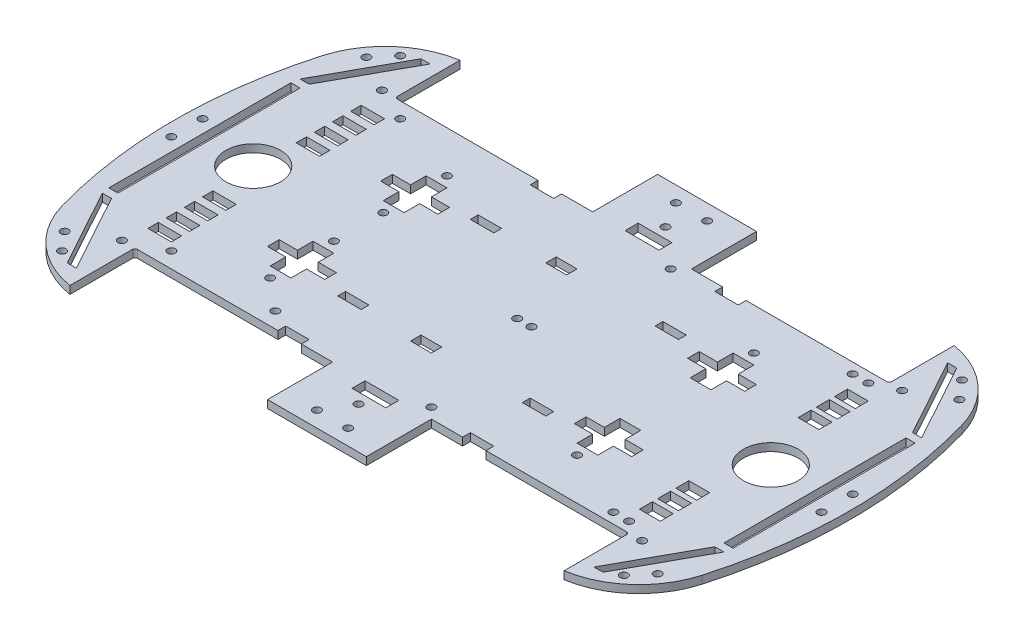
SolidWorks part; units mm, degrees
material "PMMA"
ref_plane "前视基准面" through (0, 0, 0) normal (0, 0, 1) x (1, 0, 0)
ref_plane "上视基准面" through (0, 0, 0) normal (0, 1, 0) x (1, 0, 0)
ref_plane "右视基准面" through (0, 0, 0) normal (1, 0, 0) x (0, 0, -1)
sketch "草图1" plane through (0, 0, 0) normal (0, 1, 0) x (1, 0, 0)
  line L0 (-95, 50) -> (-19, 50)
  line L1 (-95, -50) -> (95, -50) construction
  line L2 (-95, -50) -> (-95, 50) construction
  line L3 (-95, 50) -> (95, 50) construction
  line L4 (95, -50) -> (95, 50) construction
  line L5 (-95, -50) -> (95, 50) construction
  line L6 (-95, 50) -> (95, -50) construction
  line L7 (-19, 50) -> (-19, 75)
  line L8 (-19, 75) -> (19, 75)
  line L9 (19, 75) -> (19, 50)
  line L10 (19, 50) -> (95, 50)
  line L11 (95, 50) -> (95, 75)
  line L12 (-95, 50) -> (-95, 75)
  line L13 (0, 0) -> (95, 0) construction
  line L14 (95, -50) -> (95, -75)
  line L15 (-95, -50) -> (-95, -75)
  line L16 (-95, -50) -> (-19, -50)
  line L17 (-19, -75) -> (19, -75)
  line L18 (-19, -50) -> (-19, -75)
  line L19 (19, -75) -> (19, -50)
  line L20 (19, -50) -> (95, -50)
  line L21 (0, 0) -> (0, 50) construction
  line L23 (-130, -75) -> (130, -75) construction
  line L24 (-130, -75) -> (-130, 75) construction
  line L25 (-130, 75) -> (130, 75) construction
  line L26 (130, -75) -> (130, 75) construction
  line L27 (-130, -75) -> (130, 75) construction
  line L28 (-130, 75) -> (130, -75) construction
  arc A0 (-95, 75) -> (-123, 50) centre (-89.2273, 40.3546) ccw
  arc A1 (-95, -75) -> (-123, -50) centre (-89.2273, -40.3546) cw
  arc A2 (-123, 50) -> (-123, -50) centre (52.0714, 0) ccw
  arc A3 (95, -75) -> (123, -50) centre (89.2273, -40.3546) ccw
  arc A4 (123, 50) -> (123, -50) centre (-52.0714, 0) cw
  arc A5 (95, 75) -> (123, 50) centre (89.2273, 40.3546) cw
  point P0 (0, 0)
  point P12 (0, 75)
  dimension "D6" = 260
  dimension "D1" = 190
  dimension "D2" = 38
  dimension "D3" = 25
  dimension "D4" = 100
  dimension "D5" = 100
  dimension "D7" = 28
  dimension "D8" = 150
extrude "凸台-拉伸1" add sketch "草图1" along normal blind 3
sketch "草图2" plane through (0, 0, 0) normal (0, 1, 0) x (1, 0, 0)
  line L0 (-119.5, -38) -> (-116, -38)
  line L1 (-120, 35) -> (-116.5, 35)
  line L2 (-120, 35) -> (-120, -35)
  line L3 (-120, -35) -> (-116.5, -35)
  line L4 (-116.5, 35) -> (-116.5, -35)
  line L5 (-116, -38) -> (-99.5, -68)
  line L6 (-99.5, -68) -> (-103, -68)
  line L7 (-103, -68) -> (-119.5, -38)
  line L8 (-19, 50) -> (-95, 50) construction
  line L9 (0, 0) -> (130, 0) construction
  line L10 (-99.5, 68) -> (-103, 68)
  line L11 (-116, 38) -> (-99.5, 68)
  line L12 (-103, 68) -> (-119.5, 38)
  line L13 (-119.5, 38) -> (-116, 38)
  line L14 (-90, 41) -> (-99, 41)
  line L15 (-90, 41) -> (-90, 37)
  line L16 (-90, 37) -> (-99, 37)
  line L17 (-99, 41) -> (-99, 37)
  line L18 (-95, 50) -> (-95, 75) construction
  line L19 (-90, 34) -> (-99, 34)
  line L20 (-90, 30) -> (-99, 30)
  line L21 (-99, 34) -> (-99, 30)
  line L22 (-90, 34) -> (-90, 30)
  line L23 (-90, 27) -> (-99, 27)
  line L24 (-90, 23) -> (-99, 23)
  line L25 (-99, 27) -> (-99, 23)
  line L26 (-90, 27) -> (-90, 23)
  line L27 (-90, 20) -> (-99, 20)
  line L28 (-90, 16) -> (-99, 16)
  line L29 (-99, 20) -> (-99, 16)
  line L30 (-90, 20) -> (-90, 16)
  line L31 (-90, -20) -> (-90, -16)
  line L32 (-99, -20) -> (-99, -16)
  line L33 (-90, -16) -> (-99, -16)
  line L34 (-90, -20) -> (-99, -20)
  line L35 (-90, -27) -> (-90, -23)
  line L36 (-99, -27) -> (-99, -23)
  line L37 (-90, -23) -> (-99, -23)
  line L38 (-90, -27) -> (-99, -27)
  line L39 (-90, -34) -> (-90, -30)
  line L40 (-99, -34) -> (-99, -30)
  line L41 (-90, -30) -> (-99, -30)
  line L42 (-90, -34) -> (-99, -34)
  line L43 (-99, -41) -> (-99, -37)
  line L44 (-90, -37) -> (-99, -37)
  line L45 (-90, -41) -> (-90, -37)
  line L46 (-90, -41) -> (-99, -41)
  line L47 (-70, -19.5) -> (-70, -24)
  line L48 (-70, -24) -> (-63, -24)
  line L49 (-63, -24) -> (-63, -30)
  line L50 (-63, -30) -> (-55, -30)
  line L51 (-55, -30) -> (-55, -24)
  line L52 (-55, -24) -> (-48, -24)
  line L53 (-48, -24) -> (-48, -19.5)
  line L54 (-48, -19.5) -> (-55, -19.5)
  line L55 (-55, -19.5) -> (-55, -13.5)
  line L56 (-55, -13.5) -> (-63, -13.5)
  line L57 (-63, -13.5) -> (-63, -19.5)
  line L58 (-63, -19.5) -> (-70, -19.5)
  line L59 (-95, -50) -> (-19, -50) construction
  line L60 (-63, 19.5) -> (-70, 19.5)
  line L61 (-63, 13.5) -> (-63, 19.5)
  line L62 (-55, 13.5) -> (-63, 13.5)
  line L63 (-55, 19.5) -> (-55, 13.5)
  line L64 (-48, 19.5) -> (-55, 19.5)
  line L65 (-48, 24) -> (-48, 19.5)
  line L66 (-55, 24) -> (-48, 24)
  line L67 (-55, 30) -> (-55, 24)
  line L68 (-63, 30) -> (-55, 30)
  line L69 (-63, 24) -> (-63, 30)
  line L70 (-70, 24) -> (-63, 24)
  line L71 (-70, 19.5) -> (-70, 24)
  line L72 (-95, -75) -> (-95, -50) construction
  line L73 (-40, -50) -> (-31, -50)
  line L74 (-40, -50) -> (-40, -47)
  line L75 (-40, -47) -> (-31, -47)
  line L76 (-31, -50) -> (-31, -47)
  line L77 (-31, 50) -> (-31, 47)
  line L78 (-40, 47) -> (-31, 47)
  line L79 (-40, 50) -> (-40, 47)
  line L80 (-40, 50) -> (-31, 50)
  line L81 (-31, 27) -> (-31, 24)
  line L82 (-31, -27) -> (-40, -27)
  line L83 (-31, -27) -> (-31, -24)
  line L84 (-31, -24) -> (-40, -24)
  line L85 (-40, -27) -> (-40, -24)
  line L86 (-31, 24) -> (-40, 24)
  line L87 (-40, 27) -> (-40, 24)
  line L88 (-31, 27) -> (-40, 27)
  line L89 (0, 0) -> (0, 75) construction
  line L90 (19, 75) -> (-19, 75) construction
  line L91 (31, 27) -> (40, 27)
  line L92 (40, 27) -> (40, 24)
  line L93 (31, 24) -> (40, 24)
  line L94 (40, -27) -> (40, -24)
  line L95 (31, -24) -> (40, -24)
  line L96 (31, -27) -> (31, -24)
  line L97 (31, -27) -> (40, -27)
  line L98 (31, 27) -> (31, 24)
  line L99 (40, 50) -> (31, 50)
  line L100 (40, 50) -> (40, 47)
  line L101 (40, 47) -> (31, 47)
  line L102 (31, 50) -> (31, 47)
  line L103 (31, -50) -> (31, -47)
  line L104 (40, -47) -> (31, -47)
  line L105 (40, -50) -> (40, -47)
  line L106 (40, -50) -> (31, -50)
  line L107 (70, 19.5) -> (70, 24)
  line L108 (70, 24) -> (63, 24)
  line L109 (63, 24) -> (63, 30)
  line L110 (63, 30) -> (55, 30)
  line L111 (55, 30) -> (55, 24)
  line L112 (55, 24) -> (48, 24)
  line L113 (48, 24) -> (48, 19.5)
  line L114 (48, 19.5) -> (55, 19.5)
  line L115 (55, 19.5) -> (55, 13.5)
  line L116 (55, 13.5) -> (63, 13.5)
  line L117 (63, 13.5) -> (63, 19.5)
  line L118 (63, 19.5) -> (70, 19.5)
  line L119 (63, -19.5) -> (70, -19.5)
  line L120 (63, -13.5) -> (63, -19.5)
  line L121 (55, -13.5) -> (63, -13.5)
  line L122 (55, -19.5) -> (55, -13.5)
  line L123 (48, -19.5) -> (55, -19.5)
  line L124 (48, -24) -> (48, -19.5)
  line L125 (55, -24) -> (48, -24)
  line L126 (55, -30) -> (55, -24)
  line L127 (63, -30) -> (55, -30)
  line L128 (63, -24) -> (63, -30)
  line L129 (70, -24) -> (63, -24)
  line L130 (70, -19.5) -> (70, -24)
  line L163 (119.5, 38) -> (116, 38)
  line L164 (103, 68) -> (119.5, 38)
  line L165 (116, 38) -> (99.5, 68)
  line L166 (99.5, 68) -> (103, 68)
  line L167 (103, -68) -> (119.5, -38)
  line L168 (99.5, -68) -> (103, -68)
  line L169 (116, -38) -> (99.5, -68)
  line L170 (116.5, 35) -> (116.5, -35)
  line L171 (120, -35) -> (116.5, -35)
  line L172 (120, 35) -> (120, -35)
  line L173 (120, 35) -> (116.5, 35)
  line L174 (119.5, -38) -> (116, -38)
  line L175 (19, -50) -> (95, -50) construction
  line L176 (-6.5, -50) -> (6.5, -50)
  line L177 (-6.5, -50) -> (-6.5, -55)
  line L178 (-6.5, -55) -> (6.5, -55)
  line L179 (6.5, -50) -> (6.5, -55)
  line L180 (6.5, 50) -> (6.5, 55)
  line L181 (-6.5, 55) -> (6.5, 55)
  line L182 (-6.5, 50) -> (-6.5, 55)
  line L183 (-6.5, 50) -> (6.5, 50)
  line L184 (-19, -50) -> (-19, -75) construction
  line L185 (-11, -24) -> (-3, -24)
  line L186 (-11, -24) -> (-11, -28)
  line L187 (-11, -28) -> (-3, -28)
  line L188 (-3, -24) -> (-3, -28)
  line L189 (-3, 24) -> (-3, 28)
  line L190 (-11, 28) -> (-3, 28)
  line L191 (-11, 24) -> (-11, 28)
  line L192 (-11, 24) -> (-3, 24)
  line L193 (95, -50) -> (95, -75) construction
  line L194 (89, -40) -> (97, -40)
  line L195 (89, -40) -> (89, -35)
  line L196 (89, -35) -> (97, -35)
  line L197 (97, -40) -> (97, -35)
  line L198 (89, -33) -> (97, -33)
  line L199 (89, -33) -> (89, -28)
  line L200 (89, -28) -> (97, -28)
  line L201 (97, -33) -> (97, -28)
  line L202 (89, -26) -> (97, -26)
  line L203 (89, -26) -> (89, -21)
  line L204 (89, -21) -> (97, -21)
  line L205 (97, -26) -> (97, -21)
  line L206 (97, 26) -> (97, 21)
  line L207 (89, 21) -> (97, 21)
  line L208 (89, 26) -> (89, 21)
  line L209 (89, 26) -> (97, 26)
  line L210 (97, 33) -> (97, 28)
  line L211 (89, 28) -> (97, 28)
  line L212 (89, 33) -> (89, 28)
  line L213 (89, 33) -> (97, 33)
  line L214 (97, 40) -> (97, 35)
  line L215 (89, 35) -> (97, 35)
  line L216 (89, 40) -> (89, 35)
  line L217 (89, 40) -> (97, 40)
  arc A0 (-123, 50) -> (-123, -50) centre (52.0714, 0) ccw construction
  arc A1 (-123, 50) -> (-123, -50) centre (52.0714, 0) ccw construction
  arc A2 (123, -50) -> (123, 50) centre (-52.0714, 0) ccw construction
  circle A3 centre (-99.5, 0) radius 10.5
  arc A4 (123, 50) -> (123, -50) centre (-52.0714, 0) cw construction
  circle A5 centre (99.5, 0) radius 10.5
  point P6 (-116.5, 0)
  point P10 (-130, 0)
  point P11 (-120, 0)
  point P198 (130, 0)
  point P199 (116.5, 0)
  point P204 (0, -50)
  dimension "D3" = 13.5
  dimension "D9" = 21
  dimension "D1" = 70
  dimension "D2" = 3.5
  dimension "D4" = 30
  dimension "D5" = 20
  dimension "D6" = 3.5
  dimension "D7" = 99.5
  dimension "D8" = 68
  dimension "D10" = 4
  dimension "D11" = 9
  dimension "D12" = 9
  dimension "D13" = 4
  dimension "D15" = 3
  dimension "D16" = 4.5
  dimension "D17" = 7
  dimension "D18" = 8
  dimension "D19" = 8
  dimension "D20" = 7
  dimension "D21" = 6
  dimension "D22" = 6
  dimension "D23" = 20
  dimension "D24" = 20
  dimension "D25" = 9
  dimension "D26" = 3
  dimension "D27" = 55
  dimension "D28" = 9
  dimension "D29" = 3
  dimension "D30" = 20
  dimension "D31" = 13
  dimension "D32" = 5
  dimension "D33" = 8
  dimension "D34" = 4
  dimension "D35" = 8
  dimension "D36" = 22
  dimension "D37" = 8
  dimension "D38" = 5
  dimension "D39" = 6
  dimension "D40" = 10
  dimension "D42" = 2
  dimension "D14" = 4
  dimension "D41" = 3
extrude "切除-拉伸6" cut sketch "草图2" along normal up to surface (3 mm away) up to face at (0, 3, 0)
sketch "草图3" plane through (0, 0, 0) normal (0, 1, 0) x (1, 0, 0)
  line L0 (-95, -50) -> (-40, -50) construction
  line L4 (-95, -75) -> (-95, -50) construction
  line L5 (0, 0) -> (-130, 0) construction
  line L6 (-120, -35) -> (-120, 35) construction
  line L7 (-95, -50) -> (-40, -50) construction
  line L8 (0, 0) -> (0, 75) construction
  line L9 (19, 75) -> (-19, 75) construction
  line L10 (19, -75) -> (19, -50) construction
  line L11 (19, -50) -> (31, -50) construction
  line L12 (-63, 30) -> (-55, 30) construction
  line L13 (-40, 50) -> (-95, 50) construction
  line L14 (-40, 47) -> (-40, 50) construction
  line L15 (-55, 13.5) -> (-63, 13.5) construction
  line L16 (-116.5, 35) -> (-116.5, -35) construction
  line L17 (95, 50) -> (40, 50) construction
  line L18 (95, 75) -> (95, 50) construction
  arc A0 (-123, 50) -> (-123, -50) centre (52.0714, 0) ccw construction
  circle A1 centre (-108, -65) radius 1.5
  circle A2 centre (-114, -58) radius 1.5
  circle A3 centre (-114, 58) radius 1.5
  circle A4 centre (-108, 65) radius 1.5
  circle A5 centre (-100, 50) radius 1.5
  circle A6 centre (-87, 44) radius 1.5
  circle A7 centre (-100, -50) radius 1.5
  circle A8 centre (-87, -44) radius 1.5
  circle A9 centre (-59, -34) radius 1.5
  circle A10 centre (-59, -9.5) radius 1.5
  circle A11 centre (-59, 34) radius 1.5
  circle A12 centre (-59, 9.5) radius 1.5
  circle A13 centre (-47, -44) radius 1.5
  circle A14 centre (0, -59) radius 1.5
  circle A15 centre (-6, -69) radius 1.5
  circle A16 centre (6, -69) radius 1.5
  circle A17 centre (15, -46) radius 1.5
  circle A18 centre (2, 0) radius 1.5
  circle A19 centre (7.5, 0) radius 1.5
  circle A20 centre (6, 69) radius 1.5
  circle A21 centre (-6, 69) radius 1.5
  circle A22 centre (0, 59) radius 1.5
  circle A23 centre (59, -34) radius 1.5
  circle A24 centre (59, 34) radius 1.5
  circle A25 centre (85, -46) radius 1.5
  circle A26 centre (91, -46) radius 1.5
  circle A27 centre (100, -50) radius 1.5
  circle A28 centre (114, -58) radius 1.5
  circle A29 centre (108, -65) radius 1.5
  circle A30 centre (125, 6) radius 1.5
  circle A31 centre (125, -6) radius 1.5
  circle A32 centre (85, 46) radius 1.5
  circle A33 centre (91, 46) radius 1.5
  circle A34 centre (108, 65) radius 1.5
  circle A35 centre (114, 58) radius 1.5
  circle A36 centre (15, 46) radius 1.5
  circle A37 centre (-125, 6) radius 1.5
  circle A38 centre (-125, -6) radius 1.5
  circle A39 centre (100, 50) radius 1.5
  point P0 (-114, -58)
  point P1 (-108, -65)
  point P2 (-125, 6)
  point P3 (-125, -6)
  point P16 (-6, 69)
  point P17 (-108, 65)
  point P18 (-114, 58)
  point P19 (-100, -50)
  point P20 (108, -65)
  point P21 (114, -58)
  point P22 (125, -6)
  point P23 (125, 6)
  point P24 (114, 58)
  point P28 (108, 65)
  point P29 (6, 69)
  point P30 (-100, 50)
  point P32 (100, -50)
  point P33 (100, 50)
  point P34 (0, 59)
  point P37 (0, -59)
  point P39 (6, -69)
  point P40 (-6, -69)
  point P41 (15, -46)
  point P42 (-87, 44)
  point P43 (15, 46)
  point P44 (-87, -44)
  point P45 (-59, 34)
  point P48 (-59, 30)
  point P49 (-47, 44)
  point P55 (-59, -34)
  point P56 (-47, -44)
  point P57 (-59, 0)
  point P59 (-59, 13.5)
  point P60 (-59, 9.5)
  point P61 (-86.5, -4.25)
  point P62 (85, 46)
  point P63 (-59, -9.5)
  point P64 (-86.5, 4.25)
  point P67 (91, 46)
  point P70 (2, 0)
  point P71 (85, -46)
  point P72 (91, -46)
  point P73 (7.5, 0)
  point P77 (59, -34)
  point P78 (59, 34)
  dimension "D26" = 3
  dimension "D1" = 8
  dimension "D2" = 19
  dimension "D3" = 13
  dimension "D4" = 15
  dimension "D5" = 5
  dimension "D6" = 12
  dimension "D7" = 5
  dimension "D8" = 16
  dimension "D9" = 6
  dimension "D10" = 12
  dimension "D11" = 4
  dimension "D12" = 4
  dimension "D13" = 6
  dimension "D14" = 8
  dimension "D15" = 4
  dimension "D16" = 6
  dimension "D17" = 7
  dimension "D18" = 4
  dimension "D19" = 8.5
  dimension "D20" = 30
  dimension "D21" = 6
  dimension "D22" = 4
  dimension "D23" = 5.5
  dimension "D24" = 11.5
  dimension "D25" = 4
extrude "切除-拉伸7" cut sketch "草图3" along normal up to surface (3 mm away) up to face at (59, 3, -21.75)
fillet "圆角1" radius 1 4 edges at (95, 1.5, -50) (-95, 1.5, -50) (-95, 1.5, 50) (95, 1.5, 50)
